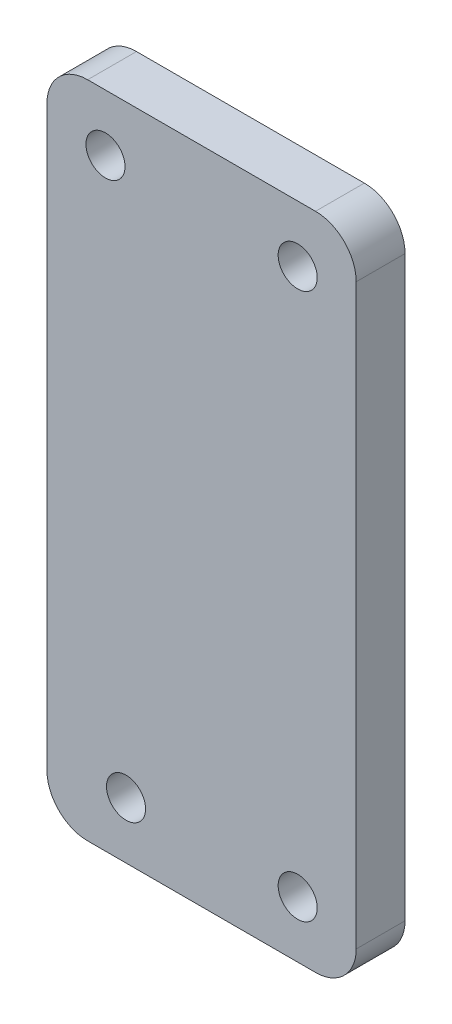
SolidWorks part; units mm, degrees
material "Custom Plastic"
ref_plane "X-Y Datum" through (0, 0, 0) normal (0, 0, 1) x (1, 0, 0)
ref_plane "X-Z Datum" through (0, 0, 0) normal (0, 1, 0) x (1, 0, 0)
ref_plane "Y-Z Datum" through (0, 0, 0) normal (1, 0, 0) x (0, 0, -1)
sketch "Sketch1" plane through (0, 0, 0) normal (0, 0, 1) x (1, 0, 0)
  line L0 (11.808, -33.542) -> (-9.2842, -33.542) construction
  line L1 (-11.8081, 33.5419) -> (11.8081, 33.5419) construction
  line L2 (-11.8081, 33.5419) -> (-11.808, -33.542) construction
  line L3 (-11.808, -33.542) -> (11.808, -33.542) construction
  line L4 (11.8081, 33.5419) -> (11.808, -33.542) construction
  line L5 (-11.8081, 33.5419) -> (11.808, -33.542) construction
  line L6 (-11.808, -33.542) -> (11.8081, 33.5419) construction
  line L7 (-19, 40.5) -> (19, 40.5)
  line L8 (-19, 40.5) -> (-19, -40.5)
  line L9 (-19, -40.5) -> (19, -40.5)
  line L10 (19, 40.5) -> (19, -40.5)
  line L11 (-19, 40.5) -> (19, -40.5) construction
  line L12 (-19, -40.5) -> (19, 40.5) construction
  circle A0 centre (-11.8081, 33.5419) radius 2 construction
  circle A1 centre (11.8081, 33.5419) radius 2 construction
  circle A5 centre (-9.2842, -33.542) radius 2 construction
  circle A6 centre (11.808, -33.542) radius 2 construction
  point P0 (0, 0)
  point P6 (0, 0)
  point P17 (0, -33.542)
  dimension "D1" = 4
  dimension "D2" = 67.0839
  dimension "D3" = 23.6161
  dimension "D4" = 38
  dimension "D5" = 81
  dimension "D6" = 21.0923
extrude "Boss-Extrude1" add sketch "Sketch1" along normal blind 6
hole_wizard "M4 Clearance Hole1" positions "Sketch7" profile "Sketch3" hole size "M4" standard "ANSI Metric" end condition through all
sketch "Sketch7" plane through (0, 0, 6) normal (0, 0, 1) x (1, 0, 0)
  point P0 (-11.8081, 33.5419)
  point P3 (11.8081, 33.5419)
  point P9 (11.808, -33.542)
  point P15 (-9.2842, -33.542)
sketch "Sketch3" plane through (-11.8081, 33.5419, 6) normal (1, 0, 0) x (0, -1, 0)
  line L0 (0, 0) -> (0, 6)
  line L1 (0, 6) -> (2.4, 6)
  line L2 (2.4, 6) -> (2.4, 0)
  line L5 (2.4, 0) -> (0, 0)
  line L11 (0, -6.35) -> (0, 107.95) construction
  dimension "Thru Hole Dia." = 4.8
  dimension "Thru Hole Depth" = 6
fillet "Fillet1" radius 5 4 edges at (-19, -40.5, 3) (19, -40.5, 3) (19, 40.5, 3) (-19, 40.5, 3)
